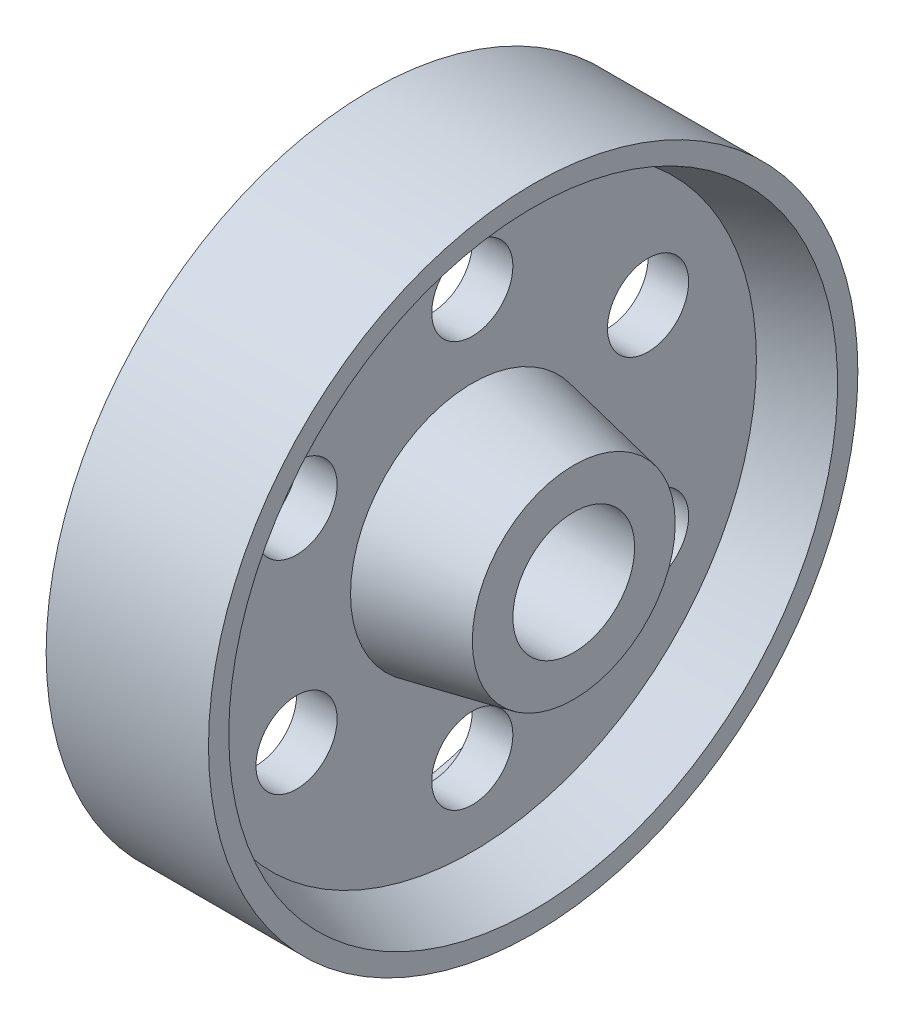
SolidWorks part; units mm, degrees
ref_plane "Front Plane" through (0, 0, 0) normal (0, 0, 1) x (1, 0, 0)
ref_plane "Top Plane" through (0, 0, 0) normal (0, 1, 0) x (1, 0, 0)
ref_plane "Right Plane" through (0, 0, 0) normal (1, 0, 0) x (0, 0, -1)
sketch "Sketch1" plane through (0, 0, 0) normal (0, 0, 1) x (1, 0, 0)
  line L0 (0, 50.8) -> (0, 9.525)
  line L1 (0, 9.525) -> (19.05, 9.525)
  line L2 (19.05, 9.525) -> (19.05, 15.875)
  line L3 (19.05, 15.875) -> (3.175, 19.05)
  line L6 (12.7, 50.8) -> (0, 50.8)
  line L7 (0, 0) -> (31.7851, 0) construction
  line L8 (12.7, 50.8) -> (12.7, 47.625)
  line L9 (12.7, 47.625) -> (3.175, 44.45)
  line L10 (3.175, 44.45) -> (3.175, 19.05)
  dimension "D1" = 19.05
  dimension "D2" = 31.75
  dimension "D3" = 38.1
  dimension "D4" = 88.9
  dimension "D5" = 95.25
  dimension "D6" = 101.6
  dimension "D7" = 12.7
  dimension "D8" = 19.05
  dimension "D9" = 3.175
revolve "Revolve1" add sketch "Sketch1" angle 360 about L7
mirror "Mirror1" about plane through (0, 50.8, 0) normal (1, 0, 0) of "Revolve1"
sketch "Sketch2" plane through (3.175, 0, 0) normal (1, 0, 0) x (0, 0, -1)
  line L0 (0, 0) -> (27.4963, 15.875) construction
  line L1 (0, 0) -> (31.75, 0) construction
  circle A0 centre (0, 0) radius 31.75 construction
  circle A1 centre (27.4963, 15.875) radius 6.35
  dimension "D2" = 12.7
  dimension "D3" = 63.5
  dimension "D1" = 30
extrude "Cut-Extrude1" cut sketch "Sketch2" against normal through all contours A1
pattern_circular "CirPattern1" count 6 over 360 about axis through (0, 0, 0) along (1, 0, 0) of "Cut-Extrude1"
